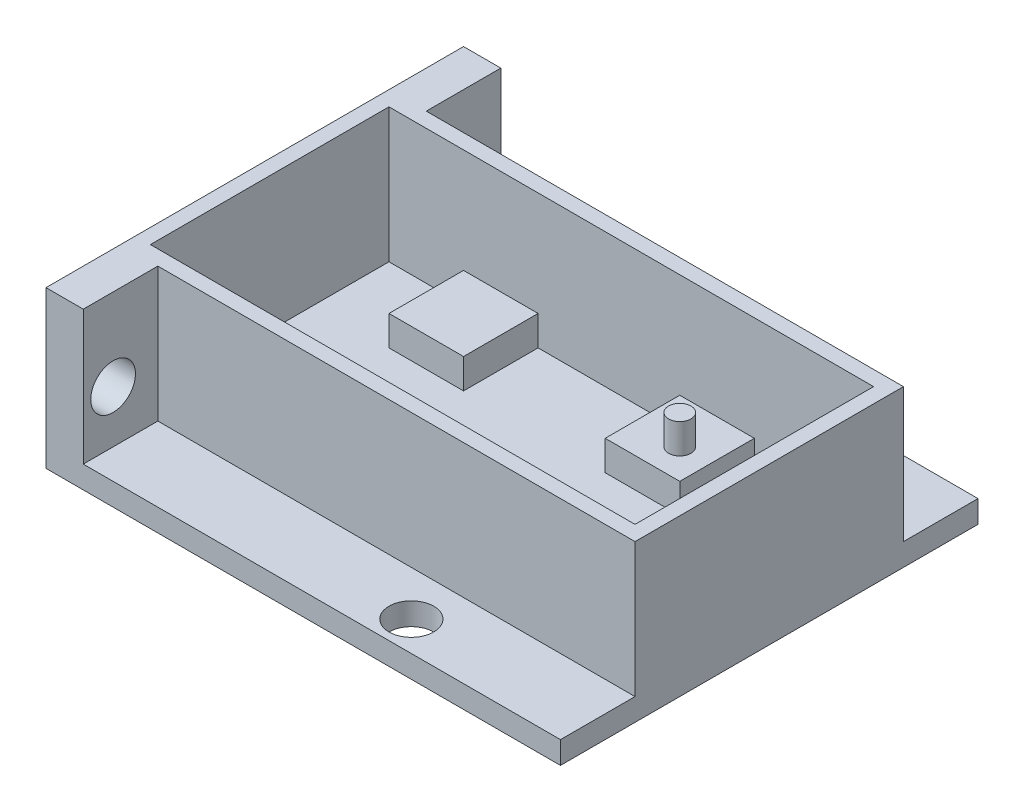
SolidWorks part; units mm, degrees
ref_plane "Front" through (0, 0, 0) normal (0, 0, 1) x (1, 0, 0)
ref_plane "Top" through (0, 0, 0) normal (0, 1, 0) x (1, 0, 0)
ref_plane "Right" through (0, 0, 0) normal (1, 0, 0) x (0, 0, -1)
sketch "Sketch1" plane through (0, 0, 0) normal (0, 1, 0) x (1, 0, 0)
  line L1 (-16.25, 8) -> (16.25, 8)
  line L2 (-16.25, 8) -> (-16.25, -8)
  line L3 (-16.25, -8) -> (16.25, -8)
  line L4 (16.25, 8) -> (16.25, -8)
  point P4 (0, 8)
  point P6 (-16.25, 0)
  dimension "D1" = 16
  dimension "D2" = 32.5
extrude "Boss-Extrude1" add sketch "Sketch1" along normal blind 1.5
sketch "Sketch3" plane through (0, 0, 0) normal (0, 1, 0) x (1, 0, 0)
  line L1 (-16.25, 8) -> (16.25, 8)
  line L2 (-16.25, 8) -> (-16.25, -8)
  line L3 (-16.25, -8) -> (16.25, -8)
  line L4 (16.25, 8) -> (16.25, -8)
  line L5 (-17.25, 9) -> (17.25, 9)
  line L6 (-17.25, 9) -> (-17.25, -9)
  line L7 (-17.25, -9) -> (17.25, -9)
  line L8 (17.25, 9) -> (17.25, -9)
  point P5 (-17.25, 0)
  point P12 (0, 9)
  dimension "D1" = 1
  dimension "D2" = 1
extrude "Boss-Extrude2" add sketch "Sketch3" along normal blind 10.5
sketch "Sketch4" plane through (0, 1.5, 0) normal (0, 1, 0) x (1, 0, 0)
  line L0 (16.25, -8) -> (16.25, 8) construction
  line L1 (8.25, 8) -> (3.25, 8)
  line L2 (8.25, 8) -> (8.25, 3)
  line L3 (8.25, 3) -> (3.25, 3)
  line L4 (3.25, 8) -> (3.25, 3)
  line L5 (8.25, -8) -> (3.25, -8)
  line L6 (8.25, -8) -> (8.25, -3)
  line L7 (8.25, -3) -> (3.25, -3)
  line L8 (3.25, -8) -> (3.25, -3)
  line L9 (-11.25, 8) -> (-6.25, 8)
  line L10 (-11.25, 8) -> (-11.25, 3)
  line L11 (-11.25, 3) -> (-6.25, 3)
  line L12 (-6.25, 8) -> (-6.25, 3)
  line L13 (-11.25, -8) -> (-6.25, -8)
  line L14 (-11.25, -8) -> (-11.25, -3)
  line L15 (-11.25, -3) -> (-6.25, -3)
  line L16 (-6.25, -8) -> (-6.25, -3)
  line L17 (16.25, 8) -> (-16.25, 8) construction
  line L18 (-16.25, -8) -> (16.25, -8) construction
  line L19 (-16.25, 8) -> (-16.25, -8) construction
  line L20 (-16.25, -8) -> (16.25, -8) construction
  dimension "D1" = 5
  dimension "D2" = 5
  dimension "D3" = 5
  dimension "D4" = 5
  dimension "D5" = 8
  dimension "D6" = 5
extrude "Boss-Extrude3" add sketch "Sketch4" along normal blind 2
sketch "Sketch6" plane through (0, 0, 0) normal (0, 1, 0) x (1, 0, 0)
  line L0 (17.25, -9) -> (17.25, 9) construction
  line L1 (-17.25, 9) -> (17.25, 9)
  line L2 (-17.25, 9) -> (-17.25, 14)
  line L3 (-17.25, 14) -> (17.25, 14)
  line L4 (17.25, 9) -> (17.25, 14)
  line L5 (-17.25, -9) -> (17.25, -9)
  line L6 (-17.25, -9) -> (-17.25, -14)
  line L7 (-17.25, -14) -> (17.25, -14)
  line L8 (17.25, -9) -> (17.25, -14)
  dimension "D1" = 5
extrude "Boss-Extrude5" add sketch "Sketch6" along normal blind 1.5
sketch "Sketch7" plane through (0, 1.5, 0) normal (0, 1, 0) x (1, 0, 0)
  line L0 (-17.25, 9) -> (17.25, 9) construction
  line L1 (-50, 0) -> (50, 0) construction
  line L2 (17.25, 9) -> (17.25, 14) construction
  circle A0 centre (5.25, 12) radius 1.5
  circle A1 centre (5.25, -12) radius 1.5
  point P4 (0, 0)
  dimension "D1" = 3
  dimension "D3" = 12
  dimension "D2" = 3
extrude "Cut-Extrude1" cut sketch "Sketch7" against normal blind 1.5
sketch "Sketch8" plane through (0, 1.5, 0) normal (0, 1, 0) x (1, 0, 0)
  line L0 (-17.25, 9) -> (17.25, 9) construction
  line L1 (-17.25, 14) -> (-14.75, 14)
  line L2 (-17.25, 14) -> (-17.25, 9)
  line L3 (-17.25, 9) -> (-14.75, 9)
  line L4 (-14.75, 14) -> (-14.75, 9)
  line L5 (-50, 0) -> (50, 0) construction
  line L6 (-17.25, -9) -> (-14.75, -9)
  line L7 (-14.75, -14) -> (-14.75, -9)
  line L8 (-17.25, -14) -> (-14.75, -14)
  line L9 (-17.25, -14) -> (-17.25, -9)
  dimension "D1" = 2.5
extrude "Boss-Extrude6" add sketch "Sketch8" along normal up to surface (9 mm away) up to face at (0, 10.5, 0)
sketch "Sketch9" plane through (-14.75, 0, 0) normal (1, 0, 0) x (0, 0, -1)
  line L0 (-14, 0) -> (14, 0) construction
  line L1 (9, 10.5) -> (9, 1.5) construction
  line L2 (0, 50) -> (0, -50) construction
  circle A0 centre (12, 5) radius 1.5
  circle A1 centre (-12, 5) radius 1.5
  dimension "D1" = 3
  dimension "D2" = 5
  dimension "D3" = 3
extrude "Cut-Extrude2" cut sketch "Sketch9" against normal through all
sketch "Sketch10" plane through (0, 3.5, 0) normal (0, 1, 0) x (1, 0, 0)
  line L0 (16.25, -8) -> (16.25, 8) construction
  line L1 (-50, 0) -> (50, 0) construction
  circle A0 centre (6.25, 5) radius 0.75
  circle A1 centre (6.25, -5) radius 0.75
  dimension "D2" = 5
  dimension "D3" = 1.5
  dimension "D1" = 10
extrude "Boss-Extrude7" add sketch "Sketch10" along normal blind 2
